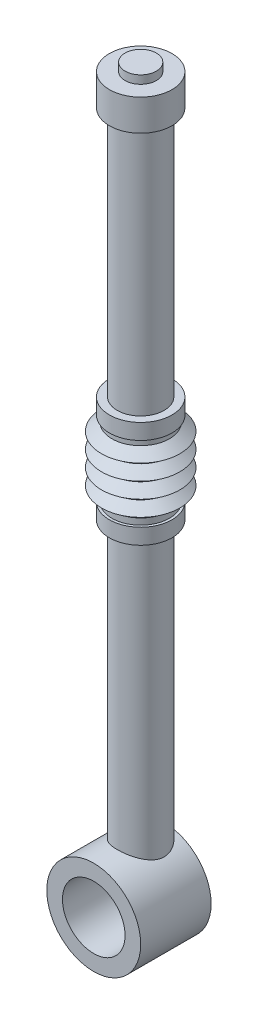
SolidWorks part; units mm, degrees
ref_plane "Front Plane" through (0, 0, 0) normal (0, 0, 1) x (1, 0, 0)
ref_plane "Top Plane" through (0, 0, 0) normal (0, 1, 0) x (1, 0, 0)
ref_plane "Right Plane" through (0, 0, 0) normal (1, 0, 0) x (0, 0, -1)
sketch "Sketch1" plane through (0, 0, 0) normal (0, 0, 1) x (1, 0, 0)
  circle A0 centre (0, 0) radius 3.175
  circle A1 centre (0, 0) radius 4.7625
  dimension "D1" = 6.35
  dimension "D2" = 1.5875
extrude "Boss-Extrude1" add sketch "Sketch1" along normal blind 4.7625 and the other way blind 2.3813
ref_plane "Plane1" through (0, 4.7625, 0) normal (0, 1, 0) x (1, 0, 0)
sketch "Sketch2" plane through (0, 4.7625, 0) normal (0, 1, 0) x (1, 0, 0)
  line L1 (4.7625, 2.3813) -> (-4.7625, 2.3813) construction
  circle A0 centre (0, 0) radius 2.3813
  dimension "D1" = 4.7625
extrude "Boss-Extrude2" add sketch "Sketch2" along normal blind 28.575 and the other way up to surface other way up to face at (4.7625, 0, -2.3813)
sketch "Sketch3" plane through (0, 0, 0) normal (1, 0, 0) x (0, 0, -1)
  line L0 (-2.921, 34.1313) -> (-2.921, 34.7662)
  line L1 (0, 32.5438) -> (-3.175, 32.5438)
  line L2 (0, 32.5438) -> (0, 34.1313)
  line L3 (0, 34.1313) -> (-3.175, 34.1313)
  line L4 (-3.175, 32.5438) -> (-3.175, 34.1313)
  line L5 (-2.921, 34.7662) -> (-3.9688, 35.56)
  line L6 (-3.9688, 35.56) -> (-2.921, 36.3537)
  line L7 (2.3813, 33.3375) -> (-2.3813, 33.3375) construction
  line L8 (-2.3813, 33.3375) -> (-2.3813, 4.7625) construction
  line L9 (-2.3813, 33.3375) -> (-2.3813, 4.7625) construction
  line L10 (-2.921, 36.3537) -> (-3.9688, 37.1475)
  line L11 (-3.9688, 37.1475) -> (-2.921, 37.9412)
  line L12 (-2.921, 37.9412) -> (-3.9688, 38.735)
  line L13 (-3.9688, 38.735) -> (-2.921, 39.5287)
  line L14 (-2.921, 39.5287) -> (-3.9687, 40.3225)
  line L15 (-3.9687, 40.3225) -> (-2.921, 41.1162)
  line L16 (-2.921, 41.1162) -> (-2.921, 41.7512)
  line L17 (-2.921, 41.7512) -> (-3.175, 41.7512)
  line L18 (-3.175, 41.7512) -> (-3.175, 43.3387)
  line L19 (-3.175, 43.3387) -> (0, 43.3387)
  line L20 (0, 43.3387) -> (0, 34.1313)
  line L21 (0, 34.1313) -> (0.014, 34.1171)
  dimension "D1" = 0.635
  dimension "D2" = 1.5875
  dimension "D3" = 0.7937
  dimension "D4" = 0.7937
  dimension "D5" = 2.3813
  dimension "D6" = 1.5875
  dimension "D7" = 0.7937
  dimension "D8" = 0.254
  dimension "D9" = 0.7937
  dimension "D10" = 1.5875
revolve "Revolve1" add sketch "Sketch3" angle 360 about L2
sketch "Sketch4" plane through (0, 43.3387, 0) normal (0, 1, 0) x (1, 0, 0)
  circle A0 centre (0, 0) radius 2.3813
  dimension "D1" = 4.7625
extrude "Boss-Extrude3" add sketch "Sketch4" along normal blind 25.4
sketch "Sketch5" plane through (0, 68.7387, 0) normal (0, 1, 0) x (1, 0, 0)
  circle A0 centre (0, 0) radius 3.175
  dimension "D1" = 6.35
extrude "Boss-Extrude4" add sketch "Sketch5" along normal blind 3.175
sketch "Sketch6" plane through (0, 71.9137, 0) normal (0, 1, 0) x (1, 0, 0)
  circle A0 centre (0, 0) radius 1.5875
  dimension "D1" = 3.175
extrude "Boss-Extrude5" add sketch "Sketch6" along normal blind 0.8318
